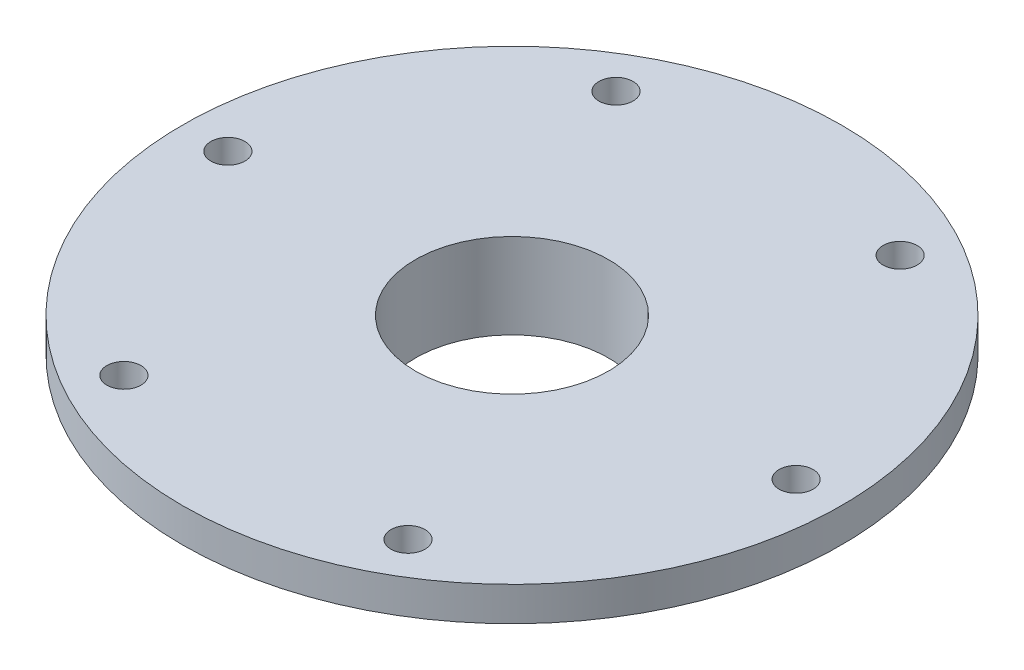
SolidWorks part; units mm, degrees
material "1060 Alloy"
ref_plane "Front Plane" through (0, 0, 0) normal (0, 0, 1) x (1, 0, 0)
ref_plane "Top Plane" through (0, 0, 0) normal (0, 1, 0) x (1, 0, 0)
ref_plane "Right Plane" through (0, 0, 0) normal (1, 0, 0) x (0, 0, -1)
sketch "Sketch4" plane through (0, 0, 0) normal (0, 0, 1) x (1, 0, 0)
  line L0 (0, 27.2792) -> (0, -44.2975) construction
  line L1 (-8.5, 0) -> (-29, 0)
  line L2 (-29, 0) -> (-29, -3)
  line L3 (-29, -3) -> (-11.75, -3)
  line L4 (-11.75, -3) -> (-11.75, -7.5)
  line L5 (-11.75, -7.5) -> (-8.5, -7.5)
  line L6 (-8.5, -7.5) -> (-8.5, 0)
  line L7 (0, 15) -> (-38, 15) construction
  line L8 (0, 20) -> (-12, 20) construction
  line L9 (-12, 20) -> (-38, 15) construction
  line L10 (-25, 17.5) -> (-25, 15) construction
  dimension "D2" = 3
  dimension "D3" = 8.5
  dimension "D4" = 11.75
  dimension "D5" = 4.5
  dimension "D6" = 15
  dimension "D7" = 38
  dimension "D8" = 12
  dimension "D9" = 5
  dimension "D1" = 29
revolve "Revolve1" add sketch "Sketch4" angle 360 about L0
sketch "Sketch5" plane through (0, 0, 0) normal (0, 1, 0) x (1, 0, 0)
  line L0 (-12, 0) -> (-38, 0) construction
  circle A0 centre (0, 0) radius 25 construction
  circle A1 centre (-25, 0) radius 1.5
  circle A2 centre (-12.5, 21.6506) radius 1.5
  circle A3 centre (12.5, 21.6506) radius 1.5
  circle A4 centre (25, 0) radius 1.5
  circle A5 centre (12.5, -21.6506) radius 1.5
  circle A6 centre (-12.5, -21.6506) radius 1.5
  circle A7 centre (0, 0) radius 12 construction
  circle A9 centre (0, 0) radius 38 construction
  point P17 (0, 0)
  dimension "D2" = 3
  dimension "D3" = 24
  dimension "D4" = 76
  dimension "D1" = 6
extrude "Cut-Extrude1" cut sketch "Sketch5" against normal through all
equation "\"Stator_OD\"= 60'No Tolerance given"
equation "\"A\"=35.81 'taken off spec sheet for 06808 (A)"
equation "\"Rotor_ID\"= 30'No Tolerance Given"
equation "\"back_bearing_Thickness\"= 5'-0.12"
equation "\"back_bearing_OD\"= 24'-0.009 https://www.mcmaster.com/5972K155/"
equation "\"Stator_Gap\"= 0.0375'+- 0.0125 (From 1.3.3.1 Kollmorgen manual)"
equation "\"Back_mount_hole\"= 1.75'To be tapped to M2 (USE LOCKTITE)"
equation "\"facePlate_Mount_Hole\"= 2.75'To be tapped to M3"
equation "\"final_shaftD\"= 12'To fit in harmonic"
equation "\"final_shaftL\"= 5.25+3+\"sheet_thick\"+\"connector_thick\"-3+\"harmon_coupleL\"+0.5-\"shaft_Ladjust\"'length to make everything nice and aligned"
equation "\"back_bearing_ID\"= 15'"
equation "\"back_bearing_IDOD\"= 16.5'measured off CAD, actually 16.75, but rounded down to nicer number"
equation "\"rotor_shaftD\"= \"Rotor_ID\" - (\"rotor-shaft_gap\")*2'"
equation "\"front_bearing_ID\"= 12'https://www.mcmaster.com/5972K154/"
equation "\"front_bearing_OD\"= 21'-0.009"
equation "\"front_bearing_IDOD\"= 13.5'Measured off CAD. Actually 13.75, but rounded down"
equation "\"front_bearing_Thickness\"= 5'-0.12"
equation "\"rotor_thickness\"= 2.4'measured off CAD"
equation "\"rotor_height\"= 32.86'+-0.075 taken off spec sheet for 06826 (C)"
equation "\"B\"= 26.3'+-0.35 taken off spec sheet for 06826"
equation "\"D3@Sketch4\" = \"back_bearing_ID\" / 2 + 1"
equation "\"D4@Sketch4\"=\"back_bearing_OD\"/2-0.25"
equation "\"D3@Sketch5\"=\"back_bearing_OD\""
equation "\"D4@Sketch5\"=\"Stator_OD\"+16"
equation "\"D7@Sketch4\" = \"Stator_OD\" / 2 + 8"
equation "\"D8@Sketch4\"=\"back_bearing_OD\"/2"
equation "\"D2@Sketch5\"=\"facePlate_Mount_Hole\"+0.25"
equation "\"rotor-shaft_gap\" = 0.0185 '+-0.0065 (from manual)"
equation "\"key_L\"= 20'-0.2 https://www.mcmaster.com/2977N19/"
equation "\"key_H\"= 4'-0.03"
equation "\"key_W\"= 4'-0.03"
equation "\"harmon_keyH\"= 13.8'+0.1 from drawing"
equation "\"harmon_coupleL\"= 21.5' taken from drawing https://www.harmonicdrive.net/_hd/content/caddownloads/dxf/csf-2uh-ulw_gearheads/CSF-17-xxx-2UH-ULW.pdf"
equation "\"harmon_diam\"= 81' from drawing"
equation "\"harmon_BCD\"= 74.5' from drawing"
equation "\"harmon_holeD1\"= 3.4' from drawing"
equation "\"harmon_holeD2\"= 3' from drawing"
equation "\"harmon_holeAng\"= 18' from drawing"
equation "\"sheet_thick\"= 1/8*25.4 'random, replace w actual sheet thickness when u feel like :)"
equation "\"nut-thickness\"= 5 'idk measure the ones in the shop and adjust"
equation "\"connector_thick\"= 10' random for now"
equation "\"shaft_Ladjust\"= 6.75' sorry. It's silly, but it works."
